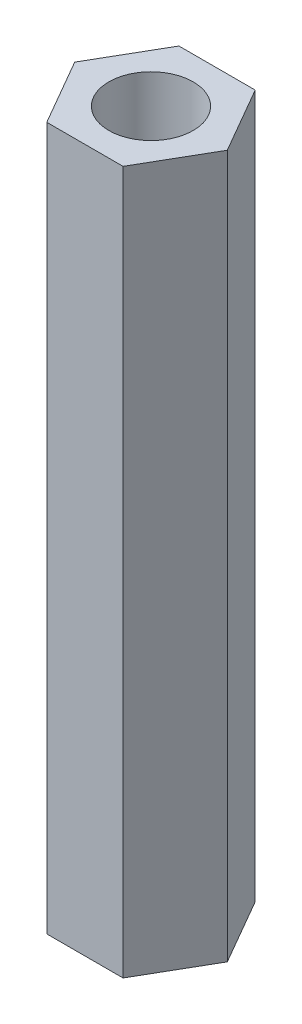
SolidWorks part; units mm, degrees
material "黄铜"
ref_plane "前视基准面" through (0, 0, 0) normal (0, 0, 1) x (1, 0, 0)
ref_plane "上视基准面" through (0, 0, 0) normal (0, 1, 0) x (1, 0, 0)
ref_plane "右视基准面" through (0, 0, 0) normal (1, 0, 0) x (0, 0, -1)
sketch "草图1" plane through (0, 0, 0) normal (0, 1, 0) x (1, 0, 0)
  line L1 (2.7135, 0) -> (1.3568, 2.35)
  line L2 (1.3568, 2.35) -> (-1.3568, 2.35)
  line L3 (-1.3568, 2.35) -> (-2.7135, 0)
  line L4 (-2.7135, 0) -> (-1.3568, -2.35)
  line L5 (-1.3568, -2.35) -> (1.3568, -2.35)
  line L6 (1.3568, -2.35) -> (2.7135, 0)
  circle A0 centre (0, 0) radius 1.5
  circle A1 centre (0, 0) radius 2.35 construction
  dimension "D1" = 3
  dimension "D2" = 4.7
extrude "凸台-拉伸1" add sketch "草图1" along normal blind 25
